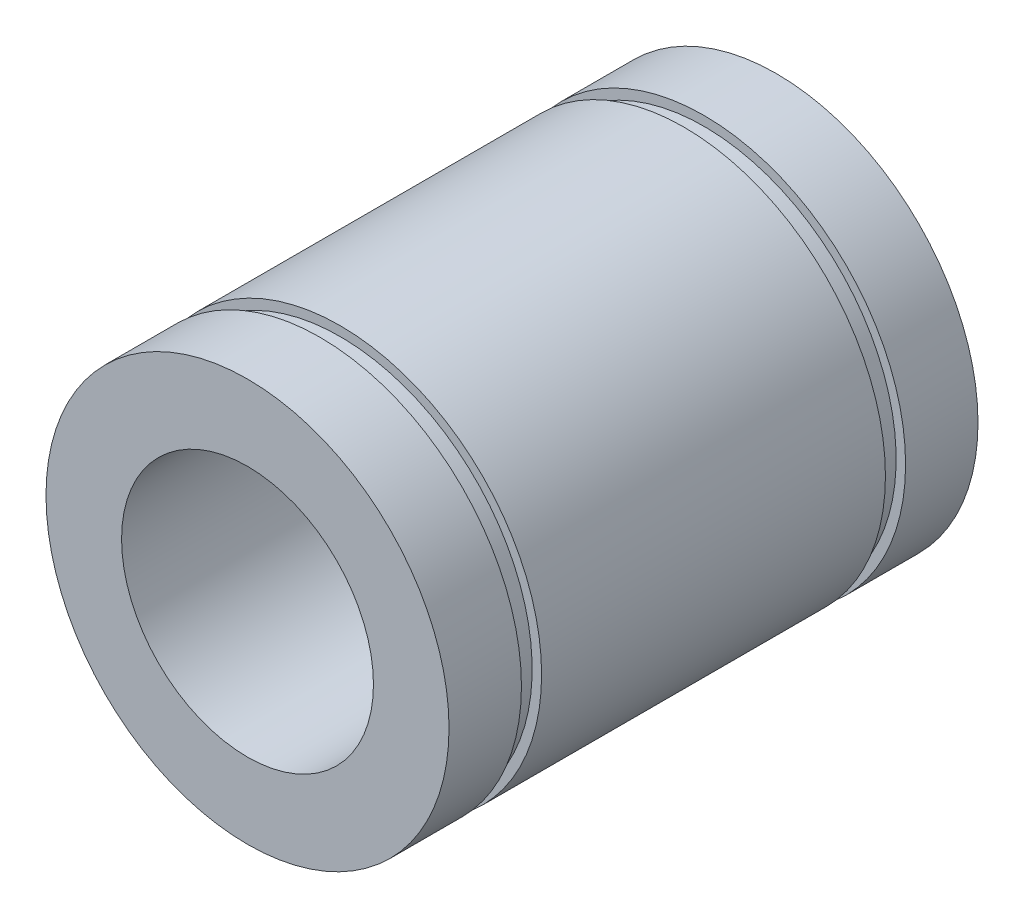
SolidWorks part; units mm, degrees
ref_plane "前视基准面" through (0, 0, 0) normal (0, 0, 1) x (1, 0, 0)
ref_plane "上视基准面" through (0, 0, 0) normal (0, 1, 0) x (1, 0, 0)
ref_plane "右视基准面" through (0, 0, 0) normal (1, 0, 0) x (0, 0, -1)
sketch "草图1" plane through (0, 0, 0) normal (0, -1, 0) x (0, 0, 1)
  line L0 (0, 0) -> (68087.4913, 0) construction
  line L1 (0, 10) -> (42, 10)
  line L2 (42, 10) -> (42, 16)
  line L3 (42, 16) -> (36.25, 16)
  line L4 (36.25, 16) -> (36.25, 15.25)
  line L5 (36.25, 15.25) -> (34.65, 15.25)
  line L6 (34.65, 15.25) -> (34.65, 16)
  line L7 (34.65, 16) -> (7.35, 16)
  line L8 (7.35, 16) -> (7.35, 15.25)
  line L9 (7.35, 15.25) -> (5.75, 15.25)
  line L10 (5.75, 15.25) -> (5.75, 16)
  line L11 (5.75, 16) -> (0, 16)
  line L12 (0, 16) -> (0, 10)
  dimension "D1" = 10
  dimension "D2" = 16
  dimension "D3" = 42
  dimension "D4" = 30.5
  dimension "D6" = 15.25
  dimension "D5" = 1.6
revolve "旋转1" add sketch "草图1" angle 360 about L0
